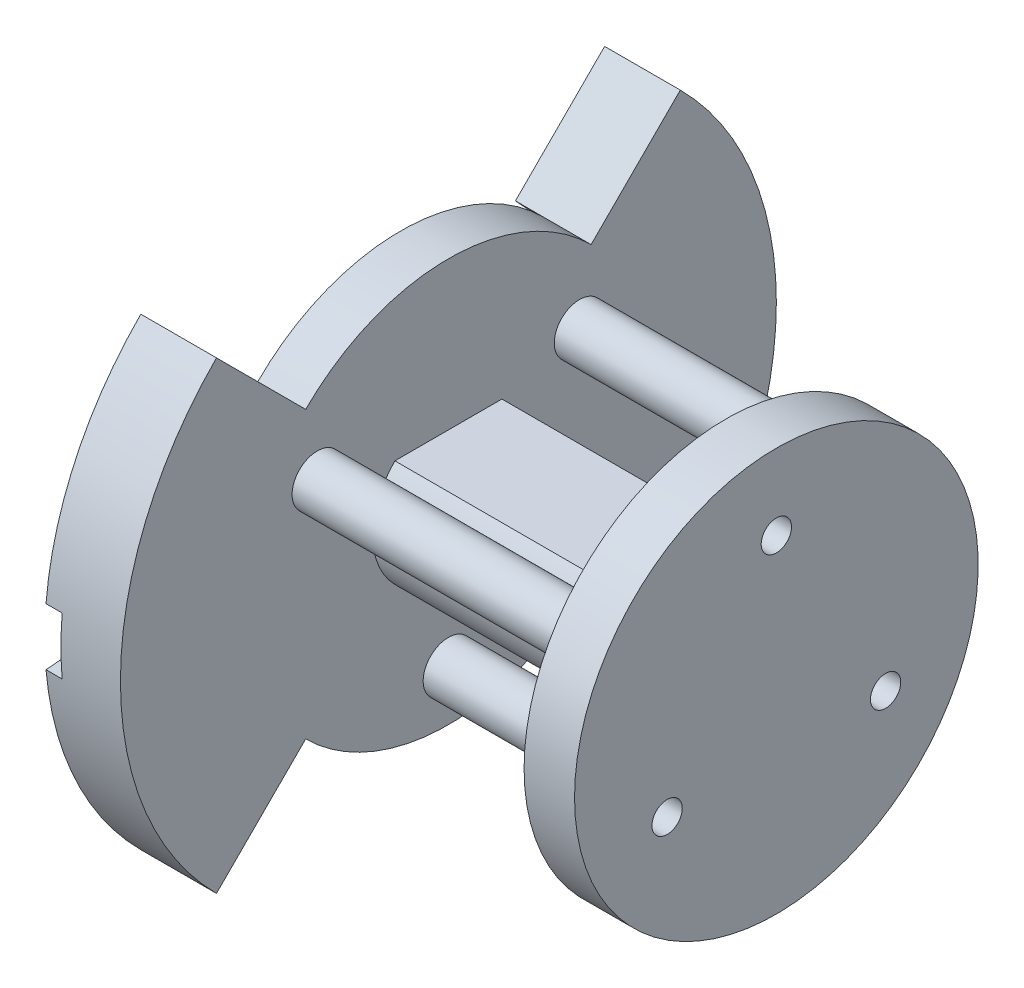
SolidWorks part; units mm, degrees
ref_plane "Alzado" through (0, 0, 0) normal (0, 0, 1) x (1, 0, 0)
ref_plane "Planta" through (0, 0, 0) normal (0, 1, 0) x (1, 0, 0)
ref_plane "Vista lateral" through (0, 0, 0) normal (1, 0, 0) x (0, 0, -1)
sketch "Croquis1" plane through (0, 0, 0) normal (0, 1, 0) x (1, 0, 0)
  line L0 (0, 0) -> (40, 0)
  line L1 (40, 0) -> (40, 20)
  line L2 (40, 20) -> (35, 20)
  line L3 (35, 20) -> (35, 7.5)
  line L4 (35, 7.5) -> (7.5, 7.5)
  line L5 (7.5, 7.5) -> (7.5, 32.5)
  line L6 (7.5, 32.5) -> (0, 32.5)
  line L7 (0, 32.5) -> (0, 20)
  line L8 (0, 20) -> (2.75, 20)
  line L9 (2.75, 20) -> (2.75, 10)
  line L10 (2.75, 10) -> (0, 10)
  line L11 (0, 10) -> (0, 0)
  dimension "D1" = 27.5
  dimension "D2" = 5
  dimension "D3" = 7.5
  dimension "D4" = 2.75
  dimension "D5" = 10
  dimension "D6" = 10
  dimension "D7" = 12.5
  dimension "D8" = 25
  dimension "D9" = 20
revolve "Revolución1" add sketch "Croquis1" angle 360 about L0
sketch "Croquis2" plane through (0, 0, 0) normal (-1, 0, 0) x (0, 0, 1)
  line L0 (0, 0) -> (22.981, 22.981)
  line L1 (-32.5, 0) -> (32.5, 0)
  line L2 (0, 0) -> (-22.981, 22.981)
  line L3 (0, 0) -> (22.981, -22.981)
  line L4 (0, 0) -> (-22.981, -22.981)
  circle A0 centre (0, 0) radius 32.5 construction
  circle A1 centre (0, 0) radius 20
  circle A2 centre (0, 0) radius 32.5
  dimension "D1" = 32.5
  dimension "D2" = 45
  dimension "D3" = 45
extrude "Cortar-Extruir2" cut sketch "Croquis2" against normal blind 7.5 contours L0 A2 L2 A1 | L4 A2 L3 A1
sketch "Croquis5" plane through (40, 0, 0) normal (1, 0, 0) x (0, 0, -1)
  circle A0 centre (0, 0) radius 12.5
  circle A1 centre (0, 12.5) radius 1.5
  circle A2 centre (10.8253, -6.25) radius 1.5
  circle A3 centre (-10.8253, -6.25) radius 1.5
  point P11 (0, 0)
  point P12 (0, 0)
  dimension "D1" = 3
  dimension "D2" = 25
  dimension "D3" = 3
extrude "Cortar-Extruir4" cut sketch "Croquis5" against normal blind 5 contours A0 A1 | A0 A1 | A0 A2 | A0 A2 | A0 A3 | A0 A3
sketch "Croquis6" plane through (40, 0, 0) normal (1, 0, 0) x (0, 0, -1)
  circle A0 centre (0, 0) radius 15
  circle A1 centre (0, -15) radius 2.5
  circle A2 centre (-12.9904, 7.5) radius 2.5
  circle A3 centre (12.9904, 7.5) radius 2.5
  point P11 (0, 0)
  point P12 (0, 0)
  dimension "D1" = 3
  dimension "D2" = 30
  dimension "D3" = 5
extrude "Saliente-Extruir1" add sketch "Croquis6" against normal blind 32.5 contours A0 A3 | A0 A3 | A0 A1 | A0 A1 | A0 A2 | A0 A2
sketch "Croquis7" plane through (0, 0, 0) normal (-1, 0, 0) x (0, 0, 1)
  line L0 (-0.7966, 3.0579) -> (-0.2353, 1.8854)
  line L1 (0, 0) -> (0, 3.74)
  line L2 (0, 5) -> (0, 5.4134)
  line L3 (0.7966, 3.0579) -> (0.2353, 1.8854)
  line L4 (1.599, 2.7256) -> (1.1668, 1.4995)
  line L5 (2.7256, 1.599) -> (1.4995, 1.1668)
  line L6 (3.0579, 0.7966) -> (1.8854, 0.2353)
  line L7 (3.0579, -0.7966) -> (1.8854, -0.2353)
  line L8 (2.7256, -1.599) -> (1.4995, -1.1668)
  line L9 (1.599, -2.7256) -> (1.1668, -1.4995)
  line L10 (0.7966, -3.0579) -> (0.2353, -1.8854)
  line L11 (-0.7966, -3.0579) -> (-0.2353, -1.8854)
  line L12 (-1.599, -2.7256) -> (-1.1668, -1.4995)
  line L13 (-2.7256, -1.599) -> (-1.4995, -1.1668)
  line L14 (-3.0579, -0.7966) -> (-1.8854, -0.2353)
  line L15 (-3.0579, 0.7966) -> (-1.8854, 0.2353)
  line L16 (-2.7256, 1.599) -> (-1.4995, 1.1668)
  line L17 (-1.599, 2.7256) -> (-1.1668, 1.4995)
  circle A0 centre (0, 0) radius 1.9
  circle A1 centre (0, 0) radius 3.16
  circle A2 centre (0, 0) radius 3.74
  circle A3 centre (0, 0) radius 5
  arc A4 (-0.7966, 3.0579) -> (-1.21, 3.5389) centre (-2.1873, 2.2806) ccw
  arc A5 (1.599, 2.7256) -> (1.6467, 3.3579) centre (0.066, 3.1593) ccw
  arc A6 (3.3579, 1.6467) -> (2.7256, 1.599) centre (3.1593, 0.066) ccw
  arc A7 (1.21, 3.5389) -> (0.7966, 3.0579) centre (2.1873, 2.2806) ccw
  arc A8 (3.0579, 0.7966) -> (3.5389, 1.21) centre (2.2806, 2.1873) ccw
  arc A9 (3.5389, -1.21) -> (3.0579, -0.7966) centre (2.2806, -2.1873) ccw
  arc A10 (2.7256, -1.599) -> (3.3579, -1.6467) centre (3.1593, -0.066) ccw
  arc A11 (1.6467, -3.3579) -> (1.599, -2.7256) centre (0.066, -3.1593) ccw
  arc A12 (0.7966, -3.0579) -> (1.21, -3.5389) centre (2.1873, -2.2806) ccw
  arc A13 (-1.21, -3.5389) -> (-0.7966, -3.0579) centre (-2.1873, -2.2806) ccw
  arc A14 (-1.599, -2.7256) -> (-1.6467, -3.3579) centre (-0.066, -3.1593) ccw
  arc A15 (-3.3579, -1.6467) -> (-2.7256, -1.599) centre (-3.1593, -0.066) ccw
  arc A16 (-3.0579, -0.7966) -> (-3.5389, -1.21) centre (-2.2806, -2.1873) ccw
  arc A17 (-3.5389, 1.21) -> (-3.0579, 0.7966) centre (-2.2806, 2.1873) ccw
  arc A18 (-2.7256, 1.599) -> (-3.3579, 1.6467) centre (-3.1593, 0.066) ccw
  arc A19 (-1.6467, 3.3579) -> (-1.599, 2.7256) centre (-0.066, 3.1593) ccw
  point P75 (0, 0)
  dimension "D1" = 3.8
  dimension "D2" = 6.32
  dimension "D3" = 7.48
  dimension "D4" = 10
  dimension "D5" = 2.42
  dimension "D6" = 1.3
  dimension "D7" = 1.3
  dimension "D8" = 8
extrude "Cortar-Extruir5" cut sketch "Croquis7" against normal blind 5
sketch "Croquis13" plane through (0, 0, 0) normal (-1, 0, 0) x (0, 0, 1)
  line L0 (22.5, 0) -> (32.5, 0)
  line L1 (-32.5, 0) -> (-22.5, 0)
  circle A0 centre (0, 0) radius 22.5
  arc A1 (22.981, -22.981) -> (22.981, 22.981) centre (0, 0) ccw construction
  arc A2 (-22.981, 22.981) -> (-22.981, -22.981) centre (0, 0) ccw construction
  circle A3 centre (27.5, 0) radius 4.25
  circle A4 centre (-27.5, 0) radius 4.125
  dimension "D1" = 8.25
  dimension "D2" = 8.5
  dimension "D3" = 5
  dimension "D4" = 27.5
extrude "Cortar-Extruir12" cut sketch "Croquis13" against normal blind 2.5 contours L1 A4 | L1 A4
sketch "Croquis14" plane through (35, 0, 0) normal (-1, 0, 0) x (0, 0, 1)
  line L0 (0, 0) -> (0, 7.5)
  line L1 (0, 0) -> (-5.3033, 5.3033)
  line L2 (0, 0) -> (5.3033, 5.3033)
  line L3 (5.3033, 5.3033) -> (-5.3033, 5.3033)
  line L4 (0, 0) -> (-5.3033, -5.3033)
  line L5 (0, 0) -> (5.3033, -5.3033)
  line L6 (-5.3033, -5.3033) -> (5.3033, -5.3033)
  circle A0 centre (0, 0) radius 7.5
  circle M7 centre (0, 0) radius 7.5
  dimension "D1" = 45
  dimension "D3" = 15
  dimension "D2" = 45
  dimension "D4" = 10.6066
extrude "Cortar-Extruir13" cut sketch "Croquis14" along normal blind 27.5 contours L3 L0 M7 | L3 L0 M7 | L6 M7
sketch "Croquis15" plane through (0, 0, 0) normal (-1, 0, 0) x (0, 0, 1)
  line L0 (0, 0) -> (32.3763, -2.8326)
  line L1 (0, 0) -> (32.3763, 2.8326)
  line L2 (0, 0) -> (0, 29)
  line L3 (0, 0) -> (0, -29)
  arc A0 (22.981, -22.981) -> (22.981, 22.981) centre (0, 0) ccw construction
  circle A1 centre (0, 0) radius 26
  circle A2 centre (0, 0) radius 29
  circle A3 centre (0, 0) radius 32.5
  arc M2 (22.981, -22.981) -> (22.981, 22.981) centre (0, 0) ccw
  dimension "D1" = 58
  dimension "D2" = 52
  dimension "D3" = 65
  dimension "D4" = 85
  dimension "D5" = 85
extrude "Cortar-Extruir14" cut sketch "Croquis15" against normal blind 1.6 contours A2 L0 L1 M2 | L0 A2 L1 A1
